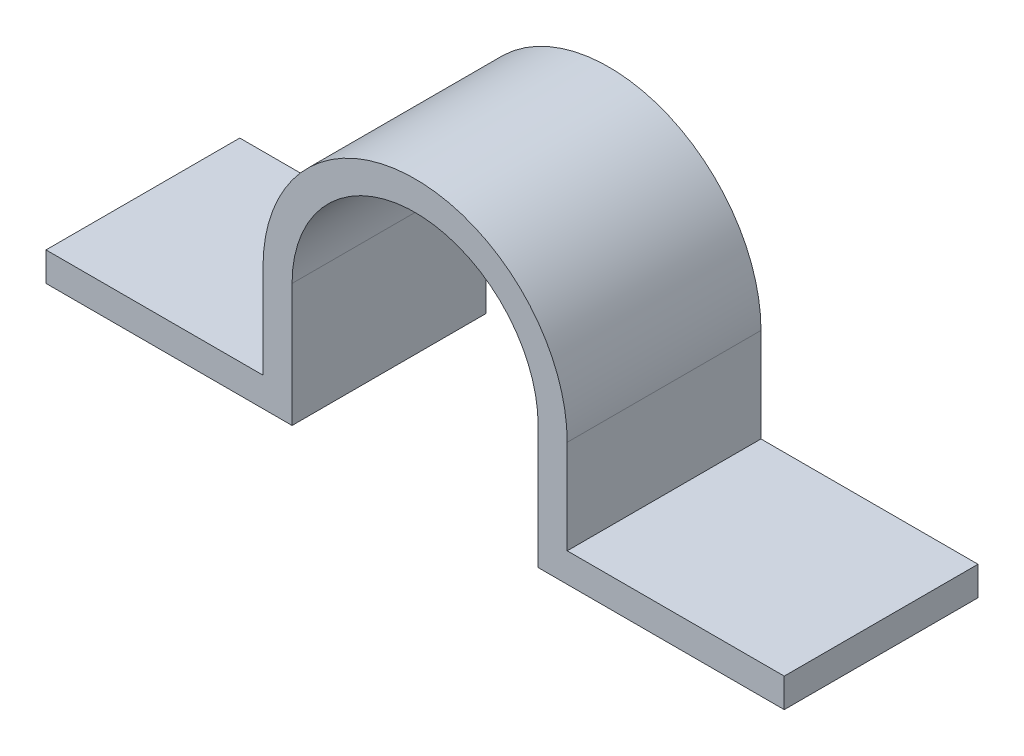
SolidWorks part; units mm, degrees
ref_plane "Front Plane" through (0, 0, 0) normal (0, 0, 1) x (1, 0, 0)
ref_plane "Top Plane" through (0, 0, 0) normal (0, 1, 0) x (1, 0, 0)
ref_plane "Right Plane" through (0, 0, 0) normal (1, 0, 0) x (0, 0, -1)
sketch "Sketch1" plane through (0, 0, 0) normal (0, 0, 1) x (1, 0, 0)
  line L0 (0, 0) -> (0, 25.4) construction
  line L1 (-38.1, 0) -> (-12.7, 0)
  line L2 (-12.7, 0) -> (-12.7, 12.7)
  line L3 (0, 25.4) -> (20.1551, 25.4) construction
  line L4 (-12.7, 0) -> (12.7, 0) construction
  line L5 (12.7, 0) -> (12.7, 12.7)
  line L6 (38.1, 0) -> (12.7, 0)
  line L7 (-12.7, 12.7) -> (0, 12.7) construction
  arc A0 (-12.7, 12.7) -> (12.7, 12.7) centre (0, 12.7) cw
  circle A1 centre (0, 12.7) radius 12.7 construction
extrude "Extrude-Thin1" add sketch "Sketch1" along normal blind 20 thin thin type one direction wall 3
